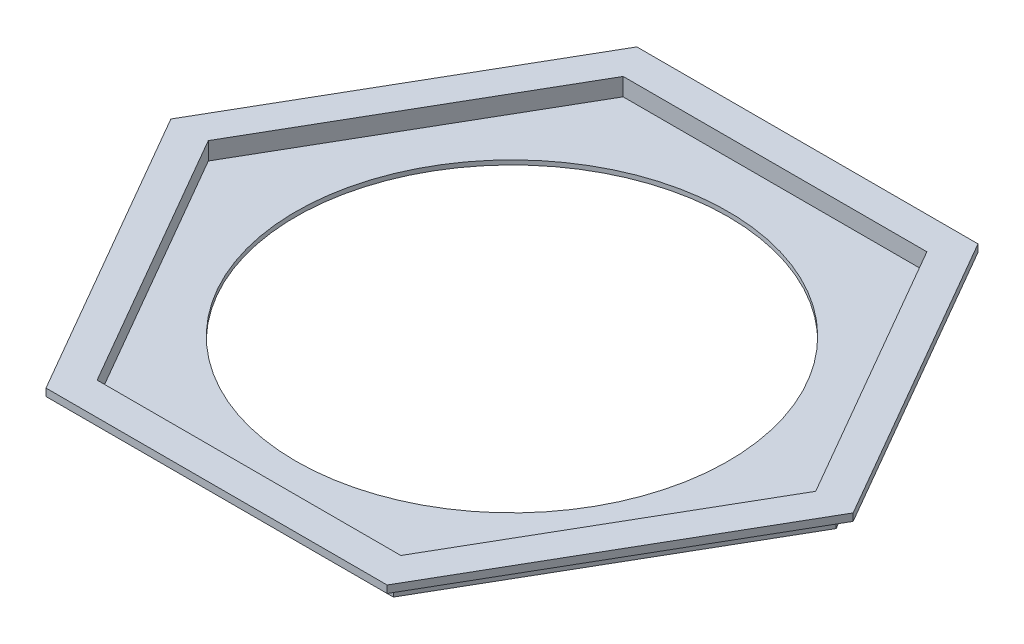
SolidWorks part; units mm, degrees
material "Ti-6Al-4VSolution treated and aged (SS)"
ref_plane "Front Plane" through (0, 0, 0) normal (0, 0, 1) x (1, 0, 0)
ref_plane "Top Plane" through (0, 0, 0) normal (0, 1, 0) x (1, 0, 0)
ref_plane "Right Plane" through (0, 0, 0) normal (1, 0, 0) x (0, 0, -1)
sketch "Sketch1" plane through (0, 0, 0) normal (0, 1, 0) x (1, 0, 0)
  line L0 (0, 0) -> (660.5894, 0) construction
  line L1 (-578.8675, 1002.6279) -> (-1157.735, 0)
  line L2 (-1157.735, 0) -> (-578.8675, -1002.6279)
  line L3 (-578.8675, -1002.6279) -> (578.8675, -1002.6279)
  line L4 (578.8675, -1002.6279) -> (1157.735, 0)
  line L5 (1157.735, 0) -> (578.8675, 1002.6279)
  line L6 (578.8675, 1002.6279) -> (-578.8675, 1002.6279)
  circle A0 centre (0, 0) radius 1002.6279 construction
  dimension "D1" = 1157.735
extrude "Boss-Extrude1" add sketch "Sketch1" against normal blind 25
sketch "Sketch3" plane through (0, -25, 0) normal (0, -1, 0) x (1, 0, 0)
  line L12 (-550, -952.6279) -> (550, -952.6279)
  line L13 (550, -952.6279) -> (1100, 0)
  line L14 (1100, 0) -> (550, 952.6279)
  line L15 (550, 952.6279) -> (-550, 952.6279)
  line L16 (-550, 952.6279) -> (-1100, 0)
  line L17 (-1100, 0) -> (-550, -952.6279)
  line L18 (-550, -952.6279) -> (550, -952.6279)
  line L19 (550, -952.6279) -> (1100, 0)
  line L20 (1100, 0) -> (550, 952.6279)
  line L21 (550, 952.6279) -> (-550, 952.6279)
  line L22 (-550, 952.6279) -> (-1100, 0)
  line L23 (-1100, 0) -> (-550, -952.6279)
  dimension "D1" = 50
extrude "Boss-Extrude2" add sketch "Sketch3" along normal blind 50
sketch "Sketch4" plane through (0, 0, 0) normal (0, 1, 0) x (1, 0, 0)
  line L12 (515.359, 892.6279) -> (-515.359, 892.6279)
  line L13 (-515.359, 892.6279) -> (-1030.718, 0)
  line L14 (-1030.718, 0) -> (-515.359, -892.6279)
  line L15 (-515.359, -892.6279) -> (515.359, -892.6279)
  line L16 (515.359, -892.6279) -> (1030.718, 0)
  line L17 (1030.718, 0) -> (515.359, 892.6279)
  line L18 (515.359, 892.6279) -> (-515.359, 892.6279)
  line L19 (-515.359, 892.6279) -> (-1030.718, 0)
  line L20 (-1030.718, 0) -> (-515.359, -892.6279)
  line L21 (-515.359, -892.6279) -> (515.359, -892.6279)
  line L22 (515.359, -892.6279) -> (1030.718, 0)
  line L23 (1030.718, 0) -> (515.359, 892.6279)
  dimension "D1" = 110
extrude "Cut-Extrude1" cut sketch "Sketch4" against normal blind 60
sketch "Sketch5" plane through (0, -60, 0) normal (0, 1, 0) x (1, 0, 0)
  circle A0 centre (0, 0) radius 733.6636
  circle A1 centre (0, 0) radius 1030.718
  dimension "D1" = 297.0544
extrude "Cut-Extrude2" cut sketch "Sketch5" against normal up to next contours A0
